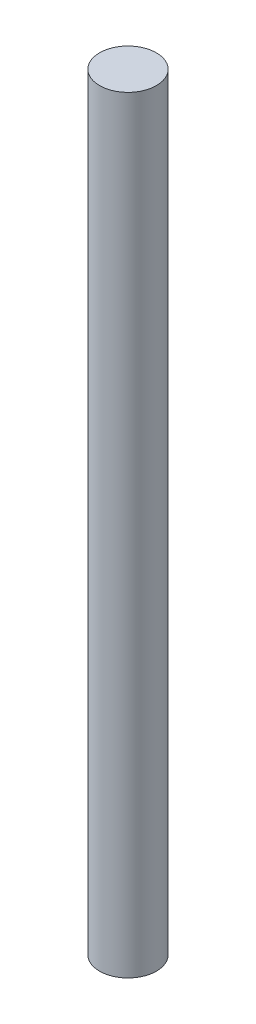
SolidWorks part; units mm, degrees
ref_plane "Front Plane" through (0, 0, 0) normal (0, 0, 1) x (1, 0, 0)
ref_plane "Top Plane" through (0, 0, 0) normal (0, 1, 0) x (1, 0, 0)
ref_plane "Right Plane" through (0, 0, 0) normal (1, 0, 0) x (0, 0, -1)
sketch "Sketch1" plane through (0, 0, 0) normal (0, 1, 0) x (1, 0, 0)
  circle A0 centre (0, 0) radius 1.5
  dimension "D1" = 3
extrude "Boss-Extrude1" add sketch "Sketch1" along normal blind 40.5
